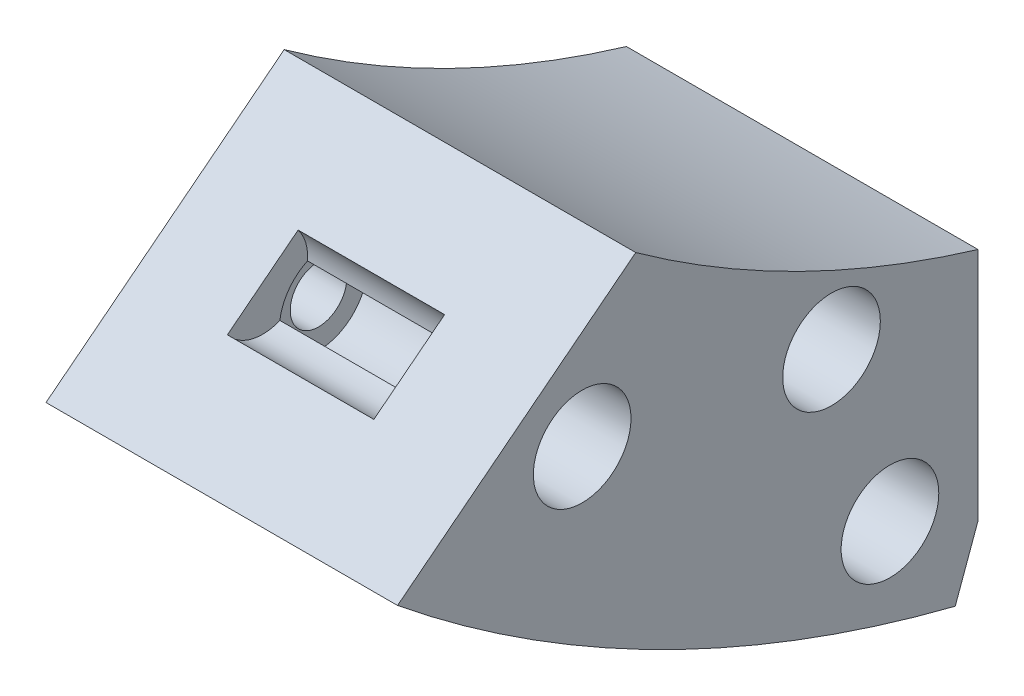
SolidWorks part; units mm, degrees
material "ABS"
ref_plane "Front Plane" through (0, 0, 0) normal (0, 0, 1) x (1, 0, 0)
ref_plane "Top Plane" through (0, 0, 0) normal (0, 1, 0) x (1, 0, 0)
ref_plane "Right Plane" through (0, 0, 0) normal (1, 0, 0) x (0, 0, -1)
sketch "Sketch1" plane through (0, 0, 0) normal (1, 0, 0) x (0, 0, -1)
  line L0 (-52.538, -1.1175) -> (-41.9314, 9.4891)
  line L1 (-7.5, 22.5) -> (7.5, 22.5)
  line L2 (-7.5, 22.5) -> (-7.5, -22.5)
  line L3 (-7.5, -22.5) -> (7.5, -22.5)
  line L4 (7.5, 22.5) -> (7.5, -22.5)
  line L5 (-7.5, 22.5) -> (7.5, -22.5) construction
  line L6 (-7.5, -22.5) -> (7.5, 22.5) construction
  line L7 (-46.7898, -6.2961) -> (-34.5937, 3.2565)
  line L8 (-27.1666, -1.2906) -> (-17.0689, 26.4527)
  line L9 (-17.0689, 26.4527) -> (-2.9735, 21.3224)
  line L10 (-2.9735, 21.3224) -> (-13.0712, -6.4209)
  line L11 (-10.0212, 23.8875) -> (-20.2818, -4.3033) construction
  line L12 (-13.0712, -6.4209) -> (-18.2346, -20.6072)
  arc A2 (-7.5, -22.5) -> (-46.7898, -6.2961) centre (0, 51.4205) cw
  arc A3 (-7.5, -7.4033) -> (-41.9314, 9.4891) centre (0, 51.4205) cw
  arc A4 (-46.7898, -6.2961) -> (-52.538, -1.1175) centre (0, 51.4205) cw
  point P0 (0, 0)
  dimension "D3" = 74.3
  dimension "D4" = 45
  dimension "D7" = 15
  dimension "D9" = 45
  dimension "D1" = 15
  dimension "D2" = 45
  dimension "D5" = 42.5
  dimension "D6" = 51.93
  dimension "D8" = 15
  dimension "D10" = 20
extrude "Boss-Extrude1" add sketch "Sketch1" along normal blind 5
sketch "Sketch2" plane through (5, 0, 0) normal (1, 0, 0) x (0, 0, -1)
  line L0 (-46.7898, -6.2961) -> (-34.5937, 3.2565)
  line L1 (-38.2267, -12.2914) -> (-25.3359, -2.1946)
  line L2 (-2.9735, 21.3224) -> (-18.2346, -20.6072) construction
  line L3 (-17.0689, 26.4527) -> (-2.9735, 21.3224)
  line L4 (-17.0689, 26.4527) -> (-26.2561, 1.2109)
  line L6 (-2.9735, 21.3224) -> (-12.1607, -3.9194)
  line L7 (-46.7898, -6.2961) -> (-34.5937, 3.2565) construction
  line L8 (-46.7898, -6.2961) -> (-34.5937, 3.2565) construction
  line L9 (-27.1666, -1.2906) -> (-17.0689, 26.4527) construction
  arc A0 (-34.5937, 3.2565) -> (-25.3359, -2.1946) centre (0, 51.4205) ccw
  arc A1 (-46.7898, -6.2961) -> (-38.2267, -12.2914) centre (0, 51.4205) ccw
  arc A2 (-34.5937, 3.2565) -> (-27.1666, -1.2906) centre (0, 51.4205) ccw construction
  arc A3 (-46.7898, -6.2961) -> (-18.2346, -20.6072) centre (0, 51.4205) ccw construction
  arc M5 (-46.7898, -6.2961) -> (-18.2346, -20.6072) centre (0, 51.4205) ccw
  arc M10 (-27.1666, -1.2906) -> (-34.5937, 3.2565) centre (0, 51.4205) cw
  line M11 (-34.5937, 3.2565) -> (-46.7898, -6.2961)
  line M21 (-17.0689, 26.4527) -> (-27.1666, -1.2906)
  line M23 (-18.2346, -20.6072) -> (-2.9735, 21.3224)
  line M24 (-2.9735, 21.3224) -> (-17.0689, 26.4527)
  dimension "D1" = 10
extrude "Boss-Extrude2" add sketch "Sketch2" along normal blind 13 contours A0 L1 M10 M11 M5 | A0 L1 M21 M5 M23 M24
sketch "Sketch3" plane through (18, 0, 0) normal (1, 0, 0) x (0, 0, -1)
  line L1 (-34.5937, 3.2565) -> (-46.7898, -6.2961) construction
  circle A0 centre (-40.6917, -1.5198) radius 2.3
  dimension "D1" = 4.6
extrude "Cut-Extrude1" cut sketch "Sketch3" along normal blind 7.5 from offset 13 offset against normal yes
sketch "Sketch8" plane through (0, 0, 0) normal (-1, 0, 0) x (0, 0, 1)
  line L0 (46.7898, -6.2961) -> (8.8144, 23.4483)
  line L1 (46.7898, -6.2961) -> (34.5937, 3.2565) construction
  line L2 (17.0689, 26.4527) -> (2.9735, 21.3224) construction
  line L3 (17.0689, 26.4527) -> (17.0689, -17.4044)
  line L5 (2.9735, 21.3224) -> (18.2346, -20.6072) construction
  circle A0 centre (0, 51.4205) radius 59.3
  line M3 (2.9735, 21.3224) -> (18.2346, -20.6072)
  line M7 (27.1666, -1.2906) -> (17.0689, 26.4527)
  line M8 (17.0689, 26.4527) -> (2.9735, 21.3224)
extrude "Cut-Extrude2" cut sketch "Sketch8" against normal through all and the other way through all contours L3 L0 M8 M3 | L3 L0 M8 | L3 L0 M7 | L3 A0 L0 M7 | A0 L3 M3
sketch "Sketch9" plane through (0, 0, 0) normal (-1, 0, 0) x (0, 0, 1)
  line L1 (46.7898, -6.2961) -> (34.5937, 3.2565) construction
  line L2 (17.0689, -17.4044) -> (18.2346, -20.6072) construction
  line L3 (17.0689, -17.4044) -> (17.0689, -5.3698) construction
  circle A0 centre (24.5689, -6.0479) radius 1.65
  circle A1 centre (37.3353, -3.9718) radius 1.65
  arc A2 (18.2346, -20.6072) -> (46.7898, -6.2961) centre (0, 51.4205) ccw construction
  circle A3 centre (21.5769, -15.1711) radius 1.65
  point P17 (17.0689, -9.6659)
  dimension "D1" = 3.3
  dimension "D2" = 62.5
  dimension "D3" = 66.8
  dimension "D4" = 7.5
  dimension "D5" = 4
  dimension "D6" = 70
  dimension "D7" = 5
hole_wizard "CBORE for M2.5 SHCS1" positions "Sketch10" profile "Sketch11" counterbore size "M2.5" standard "ANSI Metric" end condition up to next
sketch "Sketch10" plane through (18, 0, 0) normal (1, 0, 0) x (0, 0, -1)
  point P0 (-37.3353, -3.9718)
  point P3 (-24.5689, -6.0479)
  point P6 (-21.5769, -15.1711)
sketch "Sketch11" plane through (18, -3.9718, 37.3353) normal (0, 1, 0) x (0, 0, -1)
  line L0 (0, 0) -> (0, 18)
  line L1 (0, 18) -> (1.45, 18)
  line L3 (1.45, 18) -> (1.45, 13.5)
  line L4 (1.45, 13.5) -> (2.5, 13.5)
  line L5 (2.5, 13.5) -> (2.5, 0)
  line L7 (2.5, 0) -> (0, 0)
  line L11 (0, -6.35) -> (0, 107.95) construction
  dimension "Thru Hole Dia." = 2.9
  dimension "Thru Hole Depth" = 18
  dimension "C'Bore Dia." = 5
  dimension "C'Bore Depth" = 13.5
